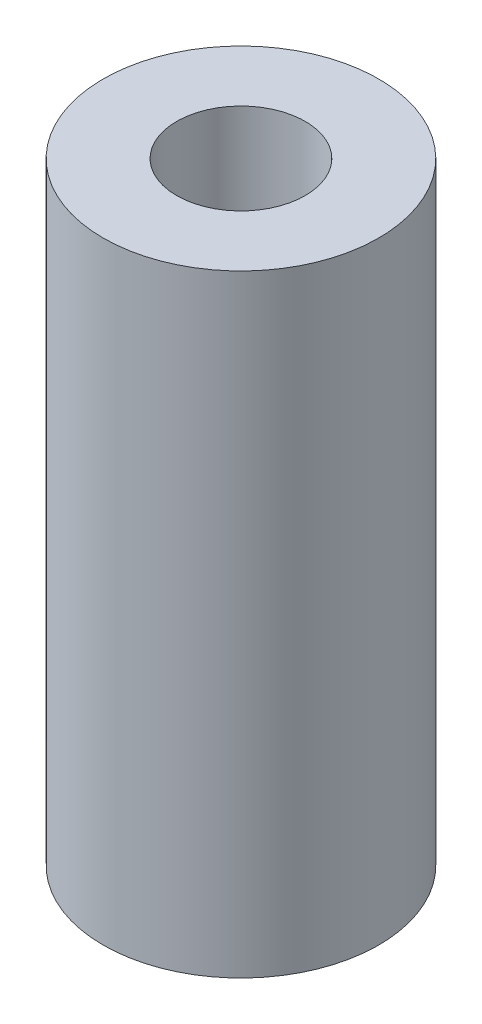
SolidWorks part; units mm, degrees
ref_plane "Front Plane" through (0, 0, 0) normal (0, 0, 1) x (1, 0, 0)
ref_plane "Top Plane" through (0, 0, 0) normal (0, 1, 0) x (1, 0, 0)
ref_plane "Right Plane" through (0, 0, 0) normal (1, 0, 0) x (0, 0, -1)
sketch "Sketch1" plane through (0, 0, 0) normal (0, 1, 0) x (1, 0, 0)
  circle A0 centre (0, 0) radius 5.715
  circle A1 centre (0, 0) radius 2.667
  dimension "D1" = 5.334
  dimension "D2" = 11.43
extrude "Boss-Extrude1" add sketch "Sketch1" along normal mid plane 25.4
